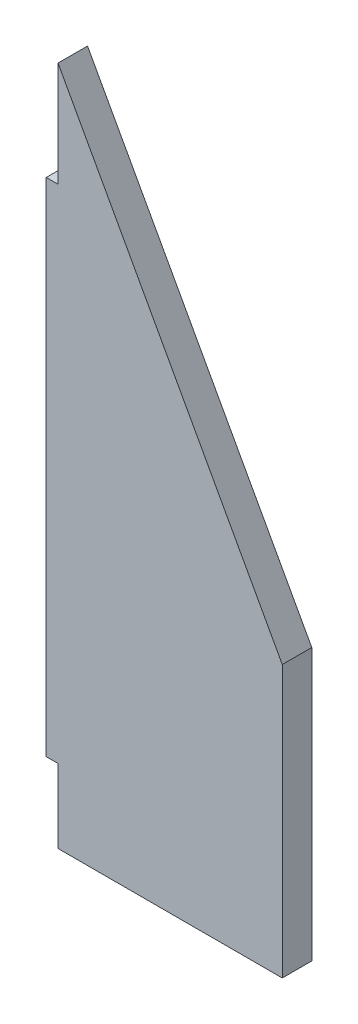
SolidWorks part; units mm, degrees
ref_plane "Front Plane" through (0, 0, 0) normal (0, 0, 1) x (1, 0, 0)
ref_plane "Top Plane" through (0, 0, 0) normal (0, 1, 0) x (1, 0, 0)
ref_plane "Right Plane" through (0, 0, 0) normal (1, 0, 0) x (0, 0, -1)
sketch "Sketch1" plane through (0, 0, 0) normal (0, 0, 1) x (1, 0, 0)
  line L0 (-2.3284, 15.8503) -> (0.2116, 15.8503)
  line L1 (0.2116, 15.8503) -> (0.2116, 0)
  line L4 (0.2116, 0) -> (48.4716, 0)
  line L5 (48.4716, 0) -> (48.4716, 58.42)
  line L6 (48.4716, 58.42) -> (0.2116, 146.3915)
  line L8 (0.2116, 146.3915) -> (0.2116, 123.8003)
  line L11 (0.2116, 123.8003) -> (-2.3284, 123.8003)
  line L12 (-2.3284, 123.8003) -> (-2.3284, 15.8503)
  point P2 (58.6824, 62.0895)
  point P3 (16.386, 126.9385)
  point P4 (14.4937, 0)
  point P10 (11.682, 123.8003)
  point P12 (48.4716, 58.7049)
  point P14 (59.135, 50.3726)
  dimension "D1" = 107.95
  dimension "D2" = 50.8
  dimension "D3" = 2.54
  dimension "D4" = 58.42
extrude "Boss-Extrude1" add sketch "Sketch1" along normal blind 6.35
